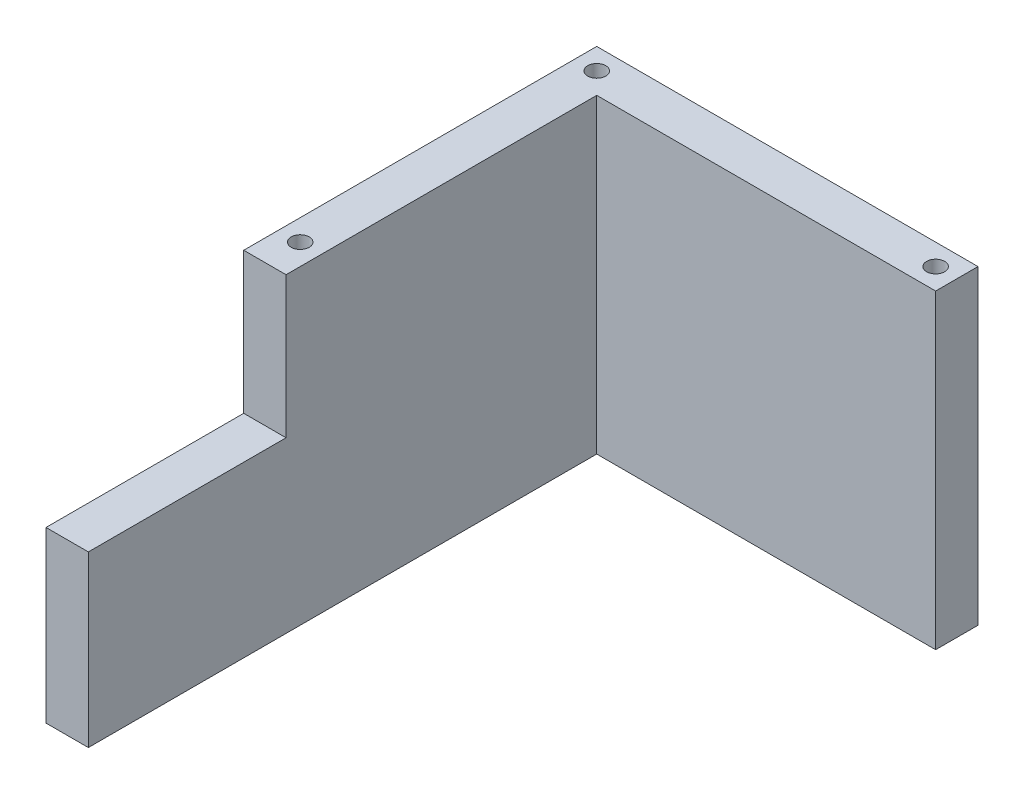
SolidWorks part; units mm, degrees
material "ABS"
ref_plane "Front Plane" through (0, 0, 0) normal (0, 0, 1) x (1, 0, 0)
ref_plane "Top Plane" through (0, 0, 0) normal (0, 1, 0) x (1, 0, 0)
ref_plane "Right Plane" through (0, 0, 0) normal (1, 0, 0) x (0, 0, -1)
sketch "Sketch1" plane through (0, 0, 0) normal (0, 1, 0) x (1, 0, 0)
  line L0 (0, 0) -> (85.725, 0)
  line L1 (85.725, 0) -> (85.725, -9.525)
  line L2 (85.725, -9.525) -> (9.525, -9.525)
  line L3 (9.525, -9.525) -> (9.525, -123.825)
  line L4 (9.525, -123.825) -> (0, -123.825)
  line L5 (0, -123.825) -> (0, 0)
  dimension "D1" = 9.525
  dimension "D2" = 9.525
  dimension "D3" = 114.3
  dimension "D4" = 76.2
extrude "Boss-Extrude1" add sketch "Sketch1" along normal blind 69.85
hole_wizard "CBORE for #4 Socket Head Cap Screw1" positions "Sketch3" profile "Sketch2" counterbore size "#4" standard "ANSI Inch"
sketch "Sketch3" plane through (0, 0, 0) normal (0, -1, 0) x (-1, 0, 0)
  line L0 (-4.7625, -123.825) -> (-4.7625, 0) construction
  line L1 (0, -123.825) -> (-9.525, -123.825) construction
  line L2 (-85.725, 0) -> (0, 0) construction
  line L4 (-85.725, -4.7625) -> (0, -4.7625) construction
  line L5 (-85.725, -9.525) -> (-85.725, 0) construction
  line L6 (0, 0) -> (0, -123.825) construction
  point P15 (-4.7625, -4.7625)
  point P17 (-4.7625, -39.6875)
  point P19 (-4.7625, -74.6125)
  point P23 (-39.6875, -4.7625)
  point P25 (-74.6125, -4.7625)
  point P27 (-4.7625, -109.5375)
  dimension "D1" = 34.925
  dimension "D2" = 34.925
  dimension "D3" = 34.925
  dimension "D4" = 34.925
  dimension "D5" = 34.925
sketch "Sketch2" plane through (4.7625, 0, 4.7625) normal (1, 0, 0) x (0, 0, -1)
  line L0 (0, 0) -> (0, 10.5056)
  line L1 (0, 10.5056) -> (1.6319, 9.525)
  line L2 (1.6319, 9.525) -> (1.6319, 4.7625)
  line L3 (1.6319, 4.7625) -> (1.9844, 4.7625)
  line L4 (1.9844, 4.7625) -> (1.9844, 0)
  line L5 (1.9844, 0) -> (0, 0)
  line L10 (0, 10.5056) -> (-1.632, 9.525) construction
  line L11 (0, -6.35) -> (0, 107.95) construction
  dimension "Hole Dia." = 3.2639
  dimension "Hole Depth" = 9.525
  dimension "C'Bore Dia." = 3.9688
  dimension "C'Bore Depth" = 4.7625
  dimension "Drill Angle" = 118
sketch "Sketch4" plane through (0, 69.85, 0) normal (0, 1, 0) x (1, 0, 0)
  line L0 (85.725, 0) -> (0, 0) construction
  line L1 (0, 0) -> (0, -123.825) construction
  circle A0 centre (4.7625, -4.7625) radius 2.032
  circle A1 centre (80.9625, -4.7625) radius 2.032
  circle A2 centre (4.7625, -71.4375) radius 2.032
  point P0 (4.7625, -4.7625)
  point P8 (80.9625, -4.7625)
  point P9 (4.7625, -71.4375)
  dimension "D7" = 4.064
  dimension "D8" = 4.064
  dimension "D9" = 4.064
  dimension "D1" = 4.7625
  dimension "D2" = 4.7625
  dimension "D3" = 4.7625
  dimension "D4" = 76.2
  dimension "D5" = 4.7625
  dimension "D6" = 66.675
extrude "Cut-Extrude1" cut sketch "Sketch4" against normal blind 4.7625
sketch "Sketch5" plane through (0, 65.0875, 0) normal (0, 1, 0) x (1, 0, 0)
  circle A0 centre (4.7625, -4.7625) radius 1.632
  circle A1 centre (80.9625, -4.7625) radius 1.632
  circle A2 centre (4.7625, -71.4375) radius 1.6319
  dimension "D1" = 3.2639
  dimension "D2" = 3.2639
  dimension "D3" = 3.2639
extrude "Cut-Extrude2" cut sketch "Sketch5" against normal blind 3.175
sketch "Sketch6" plane through (0, 0, 0) normal (-1, 0, 0) x (0, 0, 1)
  line L1 (123.825, 69.85) -> (79.375, 69.85)
  line L2 (123.825, 69.85) -> (123.825, 38.1)
  line L3 (123.825, 38.1) -> (79.375, 38.1)
  line L4 (79.375, 69.85) -> (79.375, 38.1)
  line L5 (123.825, 69.85) -> (79.375, 38.1) construction
  line L6 (123.825, 38.1) -> (79.375, 69.85) construction
  point P4 (101.6, 53.975)
  dimension "D1" = 31.75
  dimension "D2" = 44.45
extrude "Cut-Extrude3" cut sketch "Sketch6" against normal up to next
